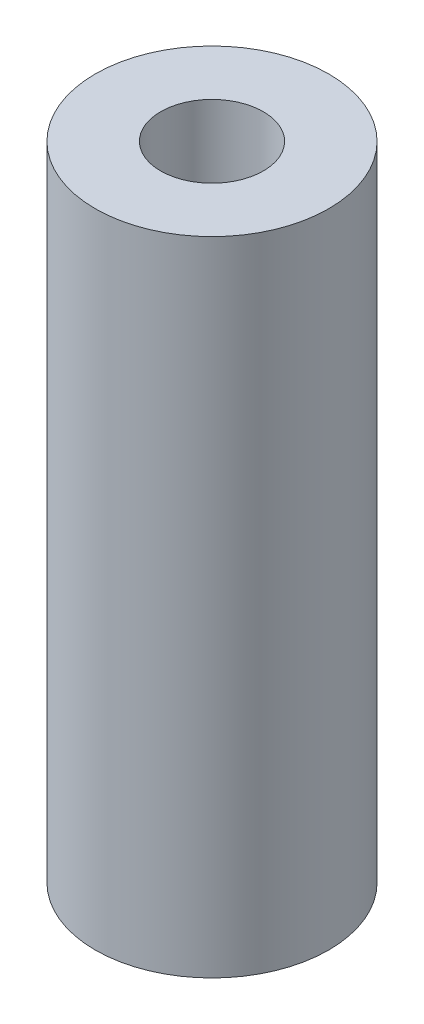
SolidWorks part; units mm, degrees
ref_plane "Front Plane" through (0, 0, 0) normal (0, 0, 1) x (1, 0, 0)
ref_plane "Top Plane" through (0, 0, 0) normal (0, 1, 0) x (1, 0, 0)
ref_plane "Right Plane" through (0, 0, 0) normal (1, 0, 0) x (0, 0, -1)
sketch "Sketch1" plane through (0, 0, 0) normal (0, 1, 0) x (1, 0, 0)
  circle A0 centre (0, 0) radius 6.35
  circle A1 centre (0, 0) radius 2.794
  dimension "D1" = 12.7
  dimension "D2" = 5.588
extrude "Boss-Extrude1" add sketch "Sketch1" along normal blind 34.925
